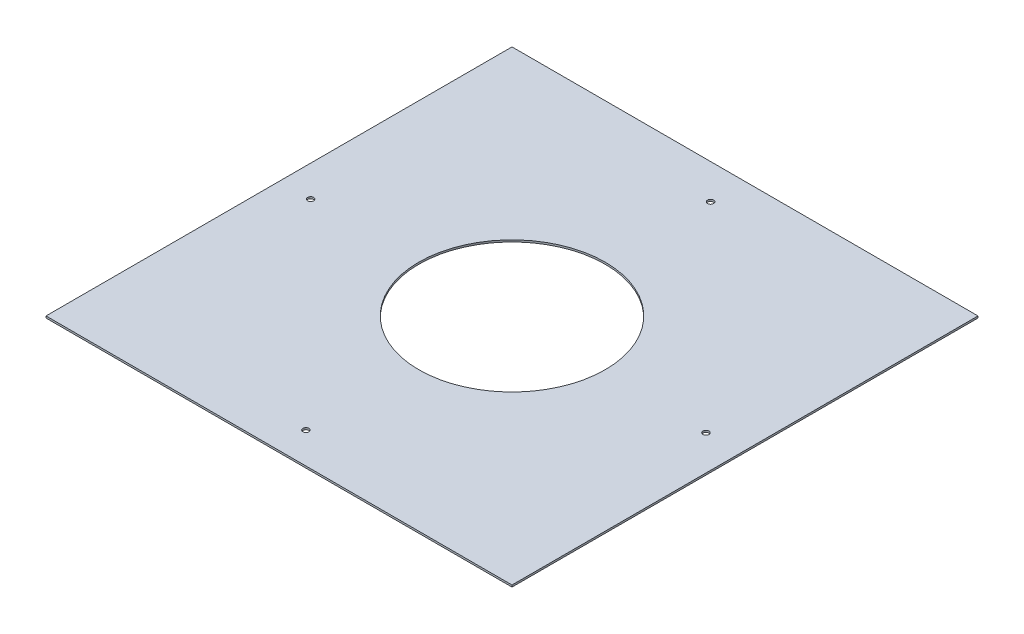
SolidWorks part; units mm, degrees
ref_plane "Front Plane" through (0, 0, 0) normal (0, 0, 1) x (1, 0, 0)
ref_plane "Top Plane" through (0, 0, 0) normal (0, 1, 0) x (1, 0, 0)
ref_plane "Right Plane" through (0, 0, 0) normal (1, 0, 0) x (0, 0, -1)
sketch "Sketch1" plane through (0, 0, 0) normal (0, 1, 0) x (1, 0, 0)
  line L1 (0, 0) -> (500, 0)
  line L2 (0, 0) -> (0, 500)
  line L3 (0, 500) -> (500, 500)
  line L4 (500, 0) -> (500, 500)
  circle A0 centre (250, 250) radius 100
  dimension "D3" = 200
  dimension "D1" = 500
  dimension "D2" = 500
  dimension "D4" = 250
  dimension "D5" = 250
extrude "Boss-Extrude1" add sketch "Sketch1" along normal blind 2 contours A0
sketch "草图1" plane through (0, 2, 0) normal (0, 1, 0) x (1, 0, 0)
  circle A0 centre (245.5, 33.4) radius 3.25 construction
  circle A1 centre (33.4, 250.5) radius 3.25 construction
  circle A2 centre (462.6, 245.5) radius 3.25 construction
  circle A3 centre (250.5, 462.6) radius 3.25 construction
  circle A4 centre (245.5, 33.4) radius 3.25
  circle A5 centre (33.4, 250.5) radius 3.25
  circle A6 centre (462.6, 245.5) radius 3.25
  circle A7 centre (250.5, 462.6) radius 3.25
extrude "切除-拉伸1" cut sketch "草图1" against normal blind 10
